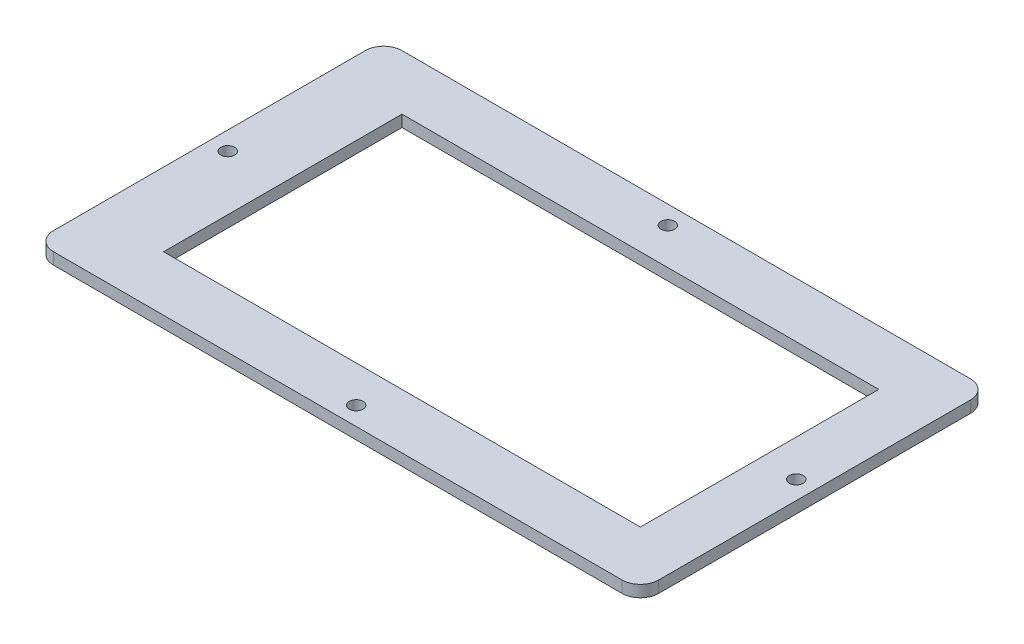
SolidWorks part; units mm, degrees
ref_plane "Front Plane" through (0, 0, 0) normal (0, 0, 1) x (1, 0, 0)
ref_plane "Top Plane" through (0, 0, 0) normal (0, 1, 0) x (1, 0, 0)
ref_plane "Right Plane" through (0, 0, 0) normal (1, 0, 0) x (0, 0, -1)
sketch "Sketch1" plane through (0, 0, 0) normal (0, 1, 0) x (1, 0, 0)
  line L0 (-165, 47.5) -> (0, 47.5) construction
  line L1 (-5, 0) -> (-160, 0)
  line L2 (0, 5) -> (0, 90)
  line L3 (-5, 95) -> (-160, 95)
  line L4 (-165, 5) -> (-165, 90)
  line L5 (-82.5, 95) -> (-82.5, 0) construction
  line L7 (-145, 80) -> (-15, 80)
  line L8 (-145, 80) -> (-145, 15)
  line L9 (-145, 15) -> (-15, 15)
  line L10 (-15, 80) -> (-15, 15)
  arc A0 (-160, 0) -> (-165, 5) centre (-160, 5) cw
  arc A1 (-5, 0) -> (0, 5) centre (-5, 5) ccw
  arc A2 (0, 90) -> (-5, 95) centre (-5, 90) ccw
  arc A3 (-160, 95) -> (-165, 90) centre (-160, 90) ccw
  circle A4 centre (-160, 47.5) radius 1.875
  circle A5 centre (-5, 47.5) radius 1.875
  circle A6 centre (-82.5, 90) radius 1.875
  circle A7 centre (-82.5, 5) radius 1.875
  point P9 (0, 0)
  dimension "D3" = 5
  dimension "D4" = 5
  dimension "D5" = 3.75
  dimension "D6" = 5
  dimension "D13" = 5
  dimension "D14" = 3.75
  dimension "D15" = 3.75
  dimension "D7" = 3.75
  dimension "D1" = 95
  dimension "D2" = 165
  dimension "D8" = 15
  dimension "D9" = 20
  dimension "D10" = 15
  dimension "D11" = 15
  dimension "D12" = 5
extrude "Boss-Extrude1" add sketch "Sketch1" along normal blind 3.175
